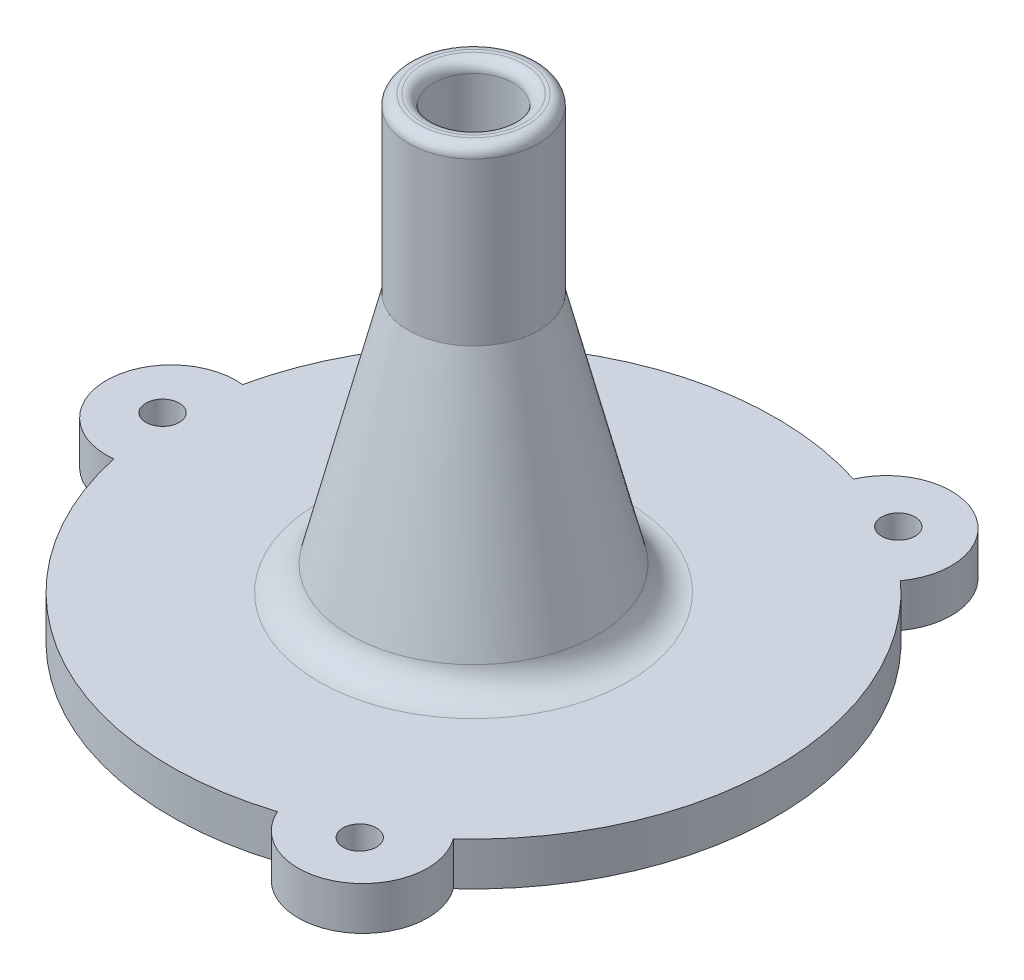
SolidWorks part; units mm, degrees
ref_plane "Front Plane" through (0, 0, 0) normal (0, 0, 1) x (1, 0, 0)
ref_plane "Top Plane" through (0, 0, 0) normal (0, 1, 0) x (1, 0, 0)
ref_plane "Right Plane" through (0, 0, 0) normal (1, 0, 0) x (0, 0, -1)
sketch "Sketch1" plane through (0, 0, 0) normal (0, 1, 0) x (1, 0, 0)
  circle A0 centre (0, 0) radius 28
  dimension "D1" = 56
extrude "Boss-Extrude1" add sketch "Sketch1" along normal blind 4
sketch "Sketch2" plane through (0, 4, 0) normal (0, 1, 0) x (1, 0, 0)
  circle A0 centre (-28, 0) radius 6
  circle A1 centre (0, 0) radius 28 construction
  circle A2 centre (14, 24.2487) radius 6
  circle A3 centre (14, -24.2487) radius 6
  point P11 (0, 0)
  dimension "D1" = 12
  dimension "D2" = 3
extrude "Boss-Extrude3" add sketch "Sketch2" against normal blind 4
sketch "Sketch3" plane through (0, 4, 0) normal (0, 1, 0) x (1, 0, 0)
  circle A0 centre (-28.8, 0) radius 1.55
  arc A1 (-27.3571, 5.9655) -> (-27.3571, -5.9655) centre (-28, 0) ccw construction
  circle A2 centre (14.4, 24.9415) radius 1.55
  circle A3 centre (14.4, -24.9415) radius 1.55
  point P11 (0, 0)
  dimension "D1" = 3.1
  dimension "D2" = 0.8
  dimension "D3" = 3
extrude "Cut-Extrude1" cut sketch "Sketch3" against normal through all
sketch "Sketch4" plane through (0, 4, 0) normal (0, 1, 0) x (1, 0, 0)
  circle A0 centre (0, 0) radius 8.8
  dimension "D1" = 17.6
extrude "Cut-Extrude2" cut sketch "Sketch4" against normal through all
sketch "Sketch5" plane through (0, 4, 0) normal (0, 1, 0) x (1, 0, 0)
  circle A0 centre (-0.0002, 0) radius 8.8 construction
  circle A1 centre (-0.0002, 0) radius 12
  dimension "D2" = 17.6
  dimension "D1" = 3.2
extrude "Boss-Extrude4" add sketch "Sketch5" along normal blind 24 draft 14
fillet "Fillet1" radius 3 1 edges at (0, 0, 8.8)
fillet "Fillet2" radius 3 1 edges at (-0.0002, 4, 12)
sketch "Sketch17" plane through (0, 4, 0) normal (0, -1, 0) x (-1, 0, 0)
  circle A0 centre (0, 0) radius 8.8
extrude "Cut-Extrude4" cut sketch "Sketch17" against normal blind 24 draft 12
sketch "Sketch19" plane through (0, 28, 0) normal (0, 1, 0) x (1, 0, 0)
  circle A0 centre (0, 0) radius 3.6986
  circle A1 centre (0, 0) radius 6.0163
extrude "Boss-Extrude10" add sketch "Sketch19" along normal blind 16
fillet "Fillet3" radius 1 2 edges at (0, 44, 3.6986) (0, 44, 6.0163)
equation "\"D1@Sketch1\"=0.8*70"
equation "\"D1@Boss-Extrude1\"=0.8*5"
equation "\"D1@Sketch2\"=0.8*15"
equation "\"D2@Sketch3\"=0.8*1"
equation "\"D1@Sketch4\"=0.8*22"
equation "\"D1@Boss-Extrude4\"=0.8*30"
equation "\"D2@Sketch5\"=0.8*22"
equation "\"D1@Cut-Extrude4\"=0.8*30"
equation "\"D1@Boss-Extrude10\"=0.8*20"
